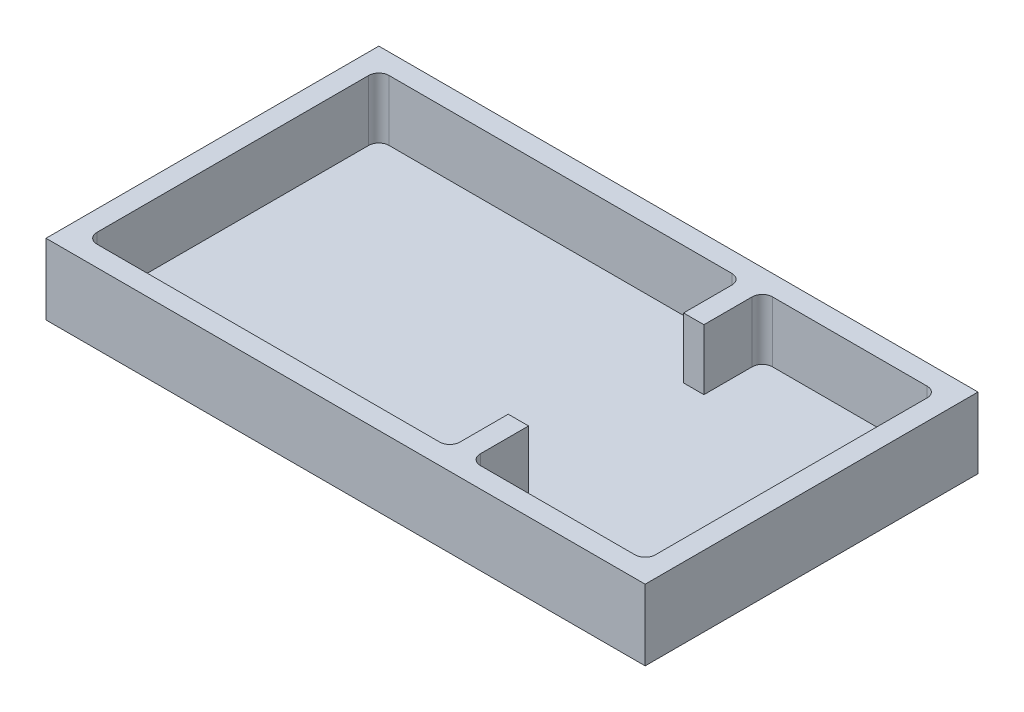
SolidWorks part; units mm, degrees
ref_plane "Front Plane" through (0, 0, 0) normal (0, 0, 1) x (1, 0, 0)
ref_plane "Top Plane" through (0, 0, 0) normal (0, 1, 0) x (1, 0, 0)
ref_plane "Right Plane" through (0, 0, 0) normal (1, 0, 0) x (0, 0, -1)
sketch "Sketch11" plane through (0, 0, 0) normal (0, 1, 0) x (1, 0, 0)
  line L0 (9.525, 6.35) -> (116.5413, 6.35)
  line L1 (0, 0) -> (187.0518, 0)
  line L2 (0, 0) -> (0, 103.9105)
  line L3 (0, 103.9105) -> (187.0518, 103.9105)
  line L4 (187.0518, 0) -> (187.0518, 103.9105)
  line L5 (180.7018, 9.525) -> (180.7018, 94.3855)
  line L6 (9.525, 97.5605) -> (116.5413, 97.5605)
  line L7 (6.35, 9.525) -> (6.35, 94.3855)
  line L8 (119.7163, 94.3855) -> (119.7163, 79.3251)
  line L9 (126.0663, 94.3855) -> (126.0663, 79.3251)
  line L10 (129.2413, 97.5605) -> (177.5268, 97.5605)
  line L11 (126.0663, 24.5854) -> (119.7163, 24.5854)
  line L12 (6.35, 97.5605) -> (180.7018, 97.5605) construction
  line L13 (119.7163, 97.5605) -> (119.7163, 6.35) construction
  line L14 (6.35, 6.35) -> (180.7018, 6.35) construction
  line L15 (126.0663, 97.5605) -> (126.0663, 6.35) construction
  line L16 (180.7018, 6.35) -> (180.7018, 97.5605) construction
  line L17 (6.35, 6.35) -> (6.35, 97.5605) construction
  line L18 (126.0663, 79.3251) -> (119.7163, 79.3251)
  line L19 (129.2413, 6.35) -> (177.5268, 6.35)
  line L20 (6.35, 51.9553) -> (180.7018, 51.9553) construction
  line L21 (126.0663, 9.525) -> (126.0663, 24.5854)
  line L22 (119.7163, 9.525) -> (119.7163, 24.5854)
  arc A0 (119.7163, 94.3855) -> (116.5413, 97.5605) centre (116.5413, 94.3855) ccw
  arc A1 (129.2413, 97.5605) -> (126.0663, 94.3855) centre (129.2413, 94.3855) ccw
  arc A2 (180.7018, 94.3855) -> (177.5268, 97.5605) centre (177.5268, 94.3855) ccw
  arc A3 (180.7018, 9.525) -> (177.5268, 6.35) centre (177.5268, 9.525) cw
  arc A4 (129.2413, 6.35) -> (126.0663, 9.525) centre (129.2413, 9.525) cw
  arc A5 (119.7163, 9.525) -> (116.5413, 6.35) centre (116.5413, 9.525) cw
  arc A6 (6.35, 94.3855) -> (9.525, 97.5605) centre (9.525, 94.3855) cw
  arc A7 (9.525, 6.35) -> (6.35, 9.525) centre (9.525, 9.525) cw
  dimension "D3" = 3.175
  dimension "D1" = 6.35
  dimension "D2" = 6.35
extrude "Extrude5" add sketch "Sketch11" along normal blind 18.923
sketch "Sketch14" plane through (0, 0, 0) normal (0, 1, 0) x (1, 0, 0)
  line L1 (0, 103.9105) -> (187.0518, 103.9105)
  line L2 (0, 103.9105) -> (0, 0)
  line L3 (0, 0) -> (187.0518, 0)
  line L4 (187.0518, 103.9105) -> (187.0518, 0)
extrude "Extrude6" add sketch "Sketch14" against normal blind 3.175
ref_plane "Plane6" through (-12.7, 0, 0) normal (-1, 0, 0) x (0, 0, 1)
sketch "Sketch15" plane through (-12.7, 0, 0) normal (-1, 0, 0) x (0, 0, 1)
  circle A0 centre (-51.9553, 7.6177) radius 6.2786
